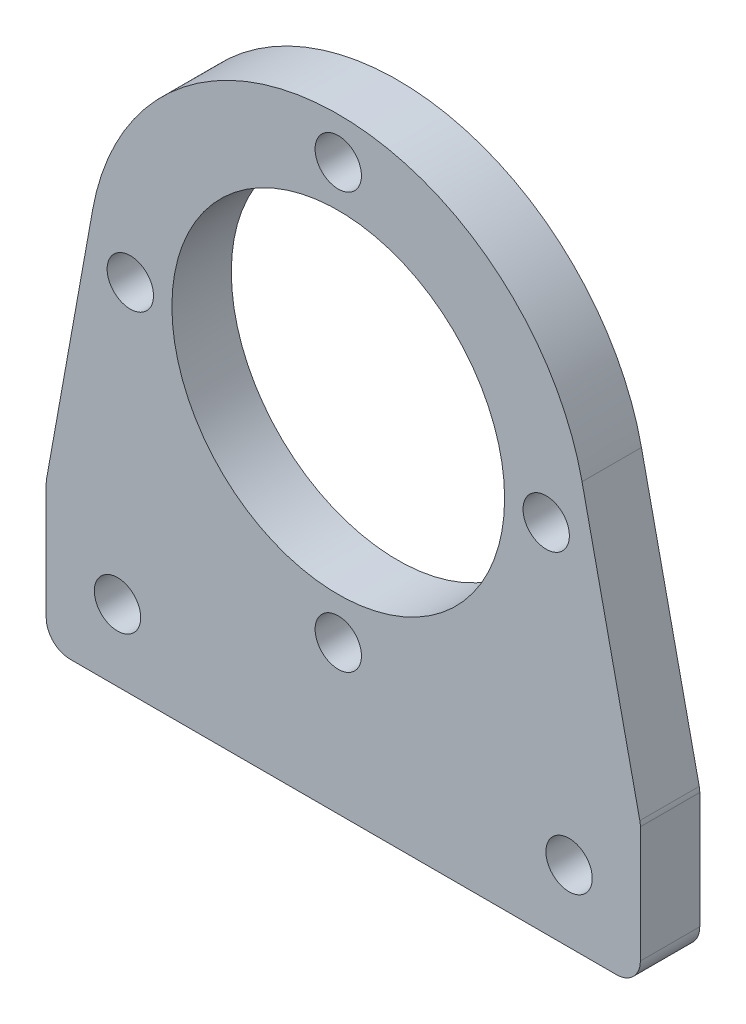
SolidWorks part; units mm, degrees
material "Thornel Mat VMA"
ref_plane "前视基准面" through (0, 0, 0) normal (0, 0, 1) x (1, 0, 0)
ref_plane "上视基准面" through (0, 0, 0) normal (0, 1, 0) x (1, 0, 0)
ref_plane "右视基准面" through (0, 0, 0) normal (1, 0, 0) x (0, 0, -1)
other "Configuration Table"
sketch "草图1" plane through (0, 0, 0) normal (0, 0, 1) x (1, 0, 0)
  line L0 (-20.6681, 3.7185) -> (-24.5757, -18)
  line L1 (-24.5757, -18) -> (-24.5757, -30)
  line L2 (-24.5757, -30) -> (25.4243, -30)
  line L3 (25.4243, -30) -> (25.4243, -18)
  line L4 (25.4243, -18) -> (20.5168, 4.4791)
  circle A0 centre (0, 0) radius 17.5 construction
  circle A1 centre (0, 17.5) radius 1.95
  circle A2 centre (17.5, 0) radius 1.95
  circle A3 centre (0, -17.5) radius 1.95
  circle A4 centre (-17.5, 0) radius 1.95
  arc A5 (20.5168, 4.4791) -> (-20.6681, 3.7185) centre (0, 0) ccw
  circle A6 centre (0, 0) radius 14
  point P5 (-70.4894, 8.5)
  dimension "D1" = 35
  dimension "D2" = 3.9
  dimension "D3" = 42
  dimension "D4" = 3.5
  dimension "D5" = 3.5
  dimension "D6" = 12
  dimension "D7" = 50
  dimension "D8" = 38.5
  dimension "D9" = 71
  dimension "D10" = 30
  dimension "D11" = 45.9137
extrude "凸台-拉伸1" add sketch "草图1" along normal blind 5
sketch "草图2" plane through (0, 0, 5) normal (0, 0, 1) x (1, 0, 0)
  line L0 (-24.5757, -24) -> (25.4243, -24) construction
  line L1 (-24.5757, -18) -> (-24.5757, -30) construction
  line L2 (25.4243, -30) -> (25.4243, -18) construction
  line L3 (-24.5757, -30) -> (25.4243, -30) construction
  circle A0 centre (19.4243, -24) radius 1.95
  circle A1 centre (-18.5757, -24) radius 1.95
  dimension "D1" = 3.9
  dimension "D2" = 6
  dimension "D3" = 6
  dimension "D4" = 6
extrude "切除-拉伸1" cut sketch "草图2" against normal through all
fillet "圆角1" radius 2 4 edges at (25.4243, -18, 2.5) (25.4243, -30, 2.5) (-24.5757, -30, 2.5) (-24.5757, -18, 2.5)
